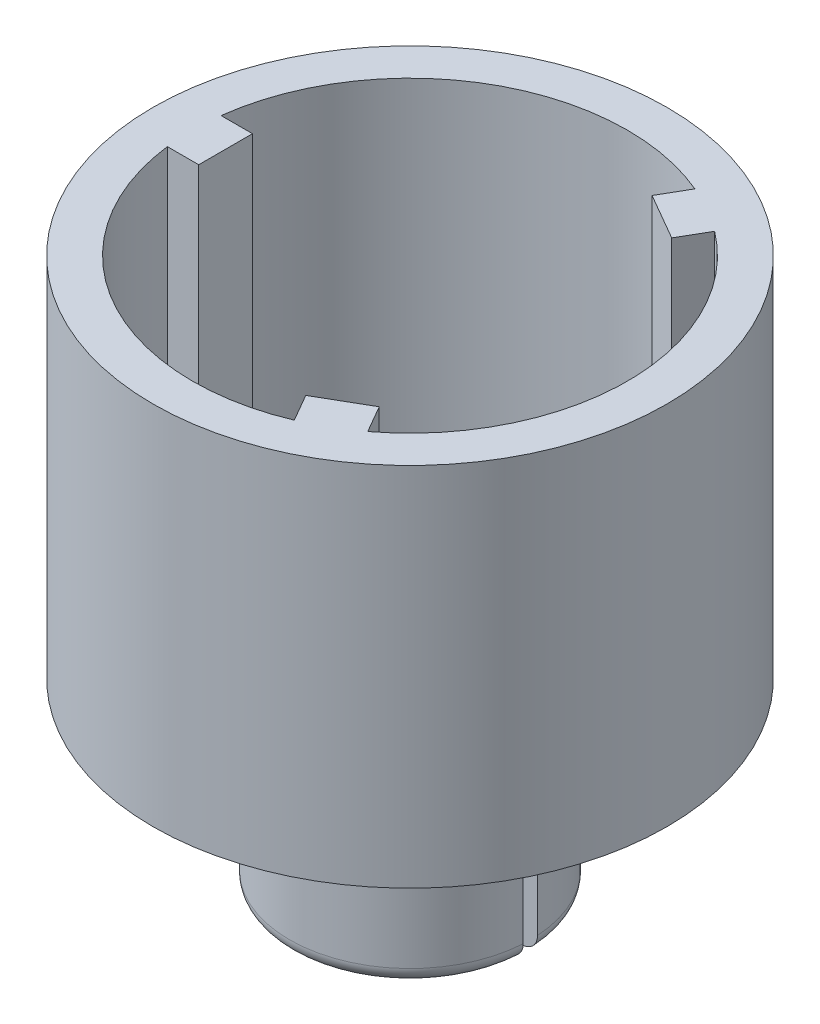
SolidWorks part; units mm, degrees
ref_plane "Front Plane" through (0, 0, 0) normal (0, 0, 1) x (1, 0, 0)
ref_plane "Top Plane" through (0, 0, 0) normal (0, 1, 0) x (1, 0, 0)
ref_plane "Right Plane" through (0, 0, 0) normal (1, 0, 0) x (0, 0, -1)
sketch "Sketch1" plane through (0, 0, 0) normal (0, 1, 0) x (1, 0, 0)
  circle A0 centre (0, 0) radius 32.5
  dimension "D1" = 65
extrude "Boss-Extrude1" add sketch "Sketch1" along normal blind 46.3
sketch "Sketch2" plane through (0, 46.3, 0) normal (0, 1, 0) x (1, 0, 0)
  circle A0 centre (0, 0) radius 27.5
  dimension "D1" = 55
extrude "Cut-Extrude1" cut sketch "Sketch2" against normal blind 40
sketch "Sketch3" plane through (0, 0, 0) normal (0, -1, 0) x (1, 0, 0)
  circle A0 centre (0, 0) radius 19.5
  dimension "D1" = 39
extrude "Boss-Extrude2" add sketch "Sketch3" along normal blind 7
sketch "Sketch4" plane through (0, -7, 0) normal (0, -1, 0) x (1, 0, 0)
  circle A0 centre (0, 0) radius 15.25
  dimension "D1" = 30.5
extrude "Boss-Extrude3" add sketch "Sketch4" along normal blind 16
fillet "Fillet1" radius 5 1 edges at (0, 0, -19.5)
sketch "Sketch7" plane through (0, -23, 0) normal (0, -1, 0) x (1, 0, 0)
  line L1 (33.0968, 0.9034) -> (-33.0968, 0.9034)
  line L2 (33.0968, 0.9034) -> (33.0968, -0.9034)
  line L3 (33.0968, -0.9034) -> (-33.0968, -0.9034)
  line L4 (-33.0968, 0.9034) -> (-33.0968, -0.9034)
  line L5 (33.0968, 0.9034) -> (-33.0968, -0.9034) construction
  line L6 (33.0968, -0.9034) -> (-33.0968, 0.9034) construction
  point P0 (0, 0)
extrude "Cut-Extrude2" cut sketch "Sketch7" against normal up to surface (16 mm away) up to face at (0, -7, -15.25)
fillet "Fillet2" radius 2 2 edges at (0, -23, 15.25) (0, -23, -15.25)
sketch "Sketch8" plane through (0, 6.3, 0) normal (0, 1, 0) x (1, 0, 0)
  circle A0 centre (0, 0) radius 7.5
  dimension "D1" = 15
sketch "Sketch9" plane through (0, 46.3, 0) normal (0, 1, 0) x (1, 0, 0)
  line L0 (0, 0) -> (-32.5, 0) construction
  line L2 (-32.3217, -3.4) -> (-23.3217, -3.4)
  line L3 (-32.3217, -3.4) -> (-32.3217, 3.4)
  line L4 (-32.3217, 3.4) -> (-23.3217, 3.4)
  line L5 (-23.3217, -3.4) -> (-23.3217, 3.4)
  circle A0 centre (0, 0) radius 32.5 construction
  point P10 (0, 0)
  dimension "D1" = 9
  dimension "D2" = 6.8
extrude "Boss-Extrude4" add sketch "Sketch9" against normal up to surface (40 mm away) up to face at (0, 6.3, 27.5)
extrude "Cut-Extrude3" cut sketch "Sketch8" against normal through all
pattern_circular "CirPattern1" count 3 over 360 about axis through (0, 0, 0) along (0, 1, 0) of "Boss-Extrude4"
